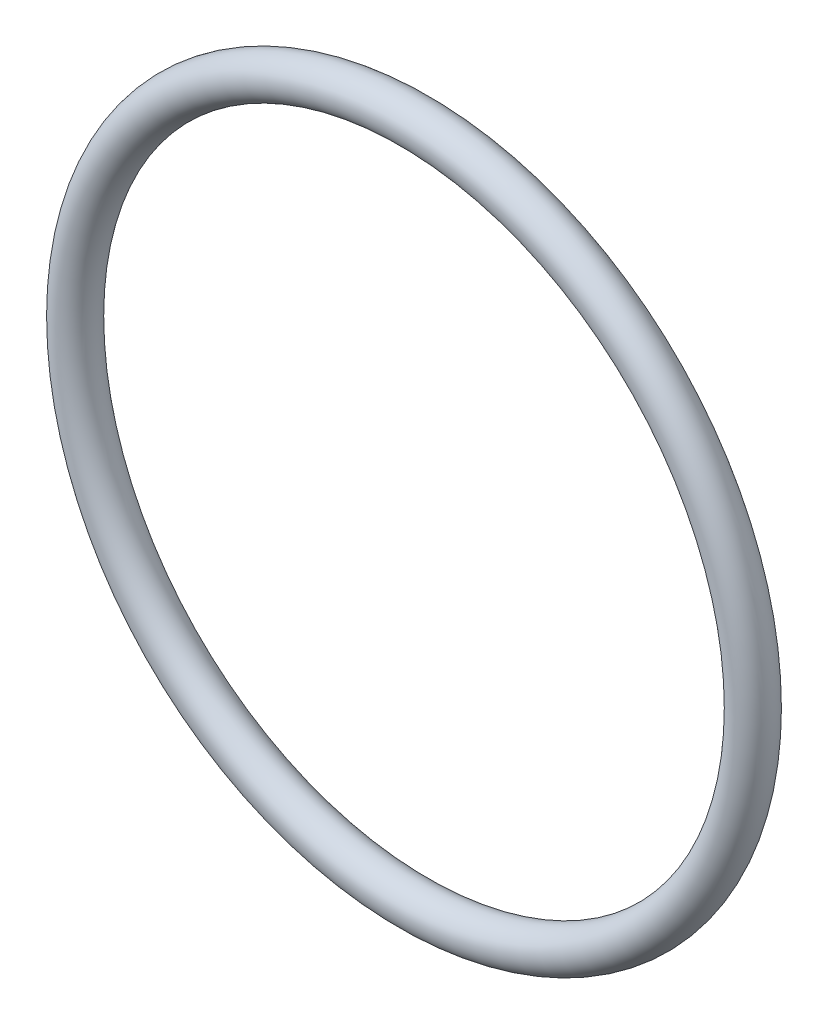
SolidWorks part; units mm, degrees
ref_plane "Front Plane" through (0, 0, 0) normal (0, 0, 1) x (1, 0, 0)
ref_plane "Top Plane" through (0, 0, 0) normal (0, 1, 0) x (1, 0, 0)
ref_plane "Right Plane" through (0, 0, 0) normal (1, 0, 0) x (0, 0, -1)
sketch "Sketch1" plane through (0, 0, 0) normal (1, 0, 0) x (0, 0, -1)
  line L0 (-15.4994, 0) -> (15.4994, 0) construction
  line L1 (0, 0) -> (0, 20.5) construction
  circle A0 centre (0, 21.8) radius 1.3
  point P4 (0, 0)
  dimension "D2" = 2.6
  dimension "D1" = 20.5
revolve "Revolve1" add sketch "Sketch1" angle 360 about L0
sketch "Sketch2" plane through (0, 0, 0) normal (0, 0, 1) x (1, 0, 0)
  circle A0 centre (0, 0) radius 21.25
  dimension "D1" = 42.5
